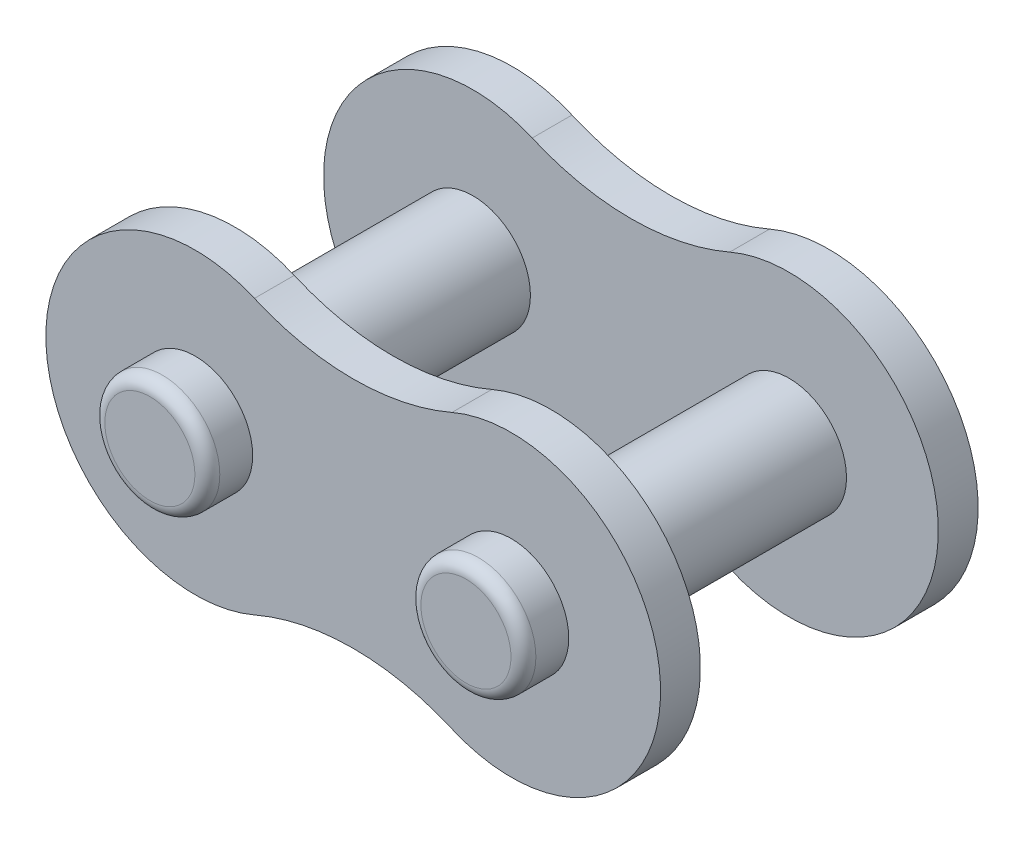
SolidWorks part; units mm, degrees
material "合金钢"
ref_plane "前视基准面" through (0, 0, 0) normal (0, 0, 1) x (1, 0, 0)
ref_plane "上视基准面" through (0, 0, 0) normal (0, 1, 0) x (1, 0, 0)
ref_plane "右视基准面" through (0, 0, 0) normal (1, 0, 0) x (0, 0, -1)
sketch "草图1" plane through (0, 0, 0) normal (0, 0, 1) x (1, 0, 0)
  line L0 (0, 0) -> (6.35, 0) construction
  line L1 (0, 0) -> (1.0014, 0) construction
  line L2 (1.0014, 0) -> (1.0014, 2.8279) construction
  line L3 (6.35, 0) -> (5.35, 0) construction
  line L4 (5.35, 0) -> (5.35, 2.8284) construction
  arc A0 (1.1906, 2.7536) -> (1.1906, -2.7536) centre (0, 0) ccw
  arc A1 (5.1594, -2.7536) -> (5.1594, 2.7536) centre (6.35, 0) ccw
  arc A2 (1.1906, 2.7536) -> (5.1594, 2.7536) centre (3.175, 7.343) ccw
  arc A3 (1.1906, -2.7536) -> (5.1594, -2.7536) centre (3.175, -7.343) cw
  dimension "D1" = 6
  dimension "D3" = 6
  dimension "D2" = 6.35
  dimension "D4" = 1
extrude "凸台-拉伸1" add sketch "草图1" along normal blind 0.8
sketch "草图2" plane through (0, 0, 0.8) normal (0, 0, 1) x (1, 0, 0)
  circle A0 centre (0, 0) radius 1.155
  circle A1 centre (6.35, 0) radius 1.155
  dimension "D1" = 2.31
  dimension "D2" = 2.31
extrude "凸台-拉伸2" add sketch "草图2" along normal blind 4.78
sketch "草图3" plane through (0, 0, 5.58) normal (0, 0, 1) x (1, 0, 0)
  arc A0 (5.1594, -2.7536) -> (1.1906, -2.7536) centre (3.175, -7.343) ccw construction
  arc A1 (5.1594, -2.7536) -> (5.1594, 2.7536) centre (6.35, 0) ccw construction
  arc A2 (1.1906, 2.7536) -> (5.1594, 2.7536) centre (3.175, 7.343) ccw construction
  arc A3 (1.1906, 2.7536) -> (1.1906, -2.7536) centre (0, 0) ccw construction
  arc A4 (5.1594, -2.7536) -> (1.1906, -2.7536) centre (3.175, -7.343) ccw
  arc A5 (5.1594, -2.7536) -> (5.1594, 2.7536) centre (6.35, 0) ccw
  arc A6 (1.1906, 2.7536) -> (5.1594, 2.7536) centre (3.175, 7.343) ccw
  arc A7 (1.1906, 2.7536) -> (1.1906, -2.7536) centre (0, 0) ccw
extrude "凸台-拉伸3" add sketch "草图3" along normal blind 0.8
sketch "草图4" plane through (0, 0, 6.38) normal (0, 0, 1) x (1, 0, 0)
  circle A0 centre (0, 0) radius 1.155
  circle A1 centre (6.35, 0) radius 1.155
  dimension "D1" = 2.31
  dimension "D2" = 2.31
extrude "凸台-拉伸4" add sketch "草图4" along normal blind 0.91
sketch "草图5" plane through (0, 0, 0) normal (0, 0, -1) x (-1, 0, 0)
  circle A0 centre (0, 0) radius 1.155
  circle A1 centre (-6.35, 0) radius 1.155
  dimension "D1" = 2.31
  dimension "D2" = 2.31
extrude "凸台-拉伸5" add sketch "草图5" along normal blind 0.91
fillet "圆角1" radius 0.25 4 edges at (-1.155, 0, -0.91) (1.155, 0, 7.29) (7.505, 0, 7.29) (5.195, 0, -0.91)
